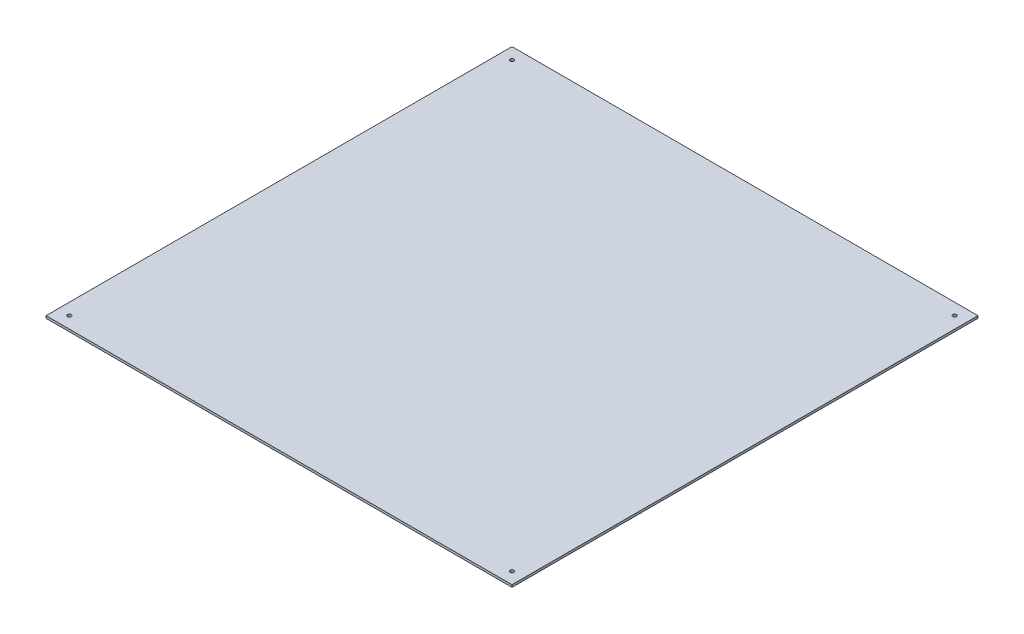
SolidWorks part; units mm, degrees
ref_plane "前视基准面" through (0, 0, 0) normal (0, 0, 1) x (1, 0, 0)
ref_plane "上视基准面" through (0, 0, 0) normal (0, 1, 0) x (1, 0, 0)
ref_plane "右视基准面" through (0, 0, 0) normal (1, 0, 0) x (0, 0, -1)
sketch "草图1" plane through (0, 0, 0) normal (0, 1, 0) x (1, 0, 0)
  line L1 (-567.9612, 366.9903) -> (432.0388, 366.9903)
  line L2 (-567.9612, 366.9903) -> (-567.9612, -633.0097)
  line L3 (-567.9612, -633.0097) -> (432.0388, -633.0097)
  line L4 (432.0388, 366.9903) -> (432.0388, -633.0097)
  dimension "D1" = 1000
  dimension "D2" = 1000
extrude "凸台-拉伸1" add sketch "草图1" along normal blind 5
sketch "草图2" plane through (0, 5, 0) normal (0, 1, 0) x (1, 0, 0)
  line L0 (432.0388, -633.0097) -> (432.0388, 366.9903) construction
  line L1 (432.0388, 366.9903) -> (-567.9612, 366.9903) construction
  line L2 (-567.9612, 366.9903) -> (-567.9612, -633.0097) construction
  line L3 (-567.9612, -633.0097) -> (432.0388, -633.0097) construction
  point P0 (407.0388, 341.9903)
  point P7 (-542.9612, -608.0097)
  point P8 (-542.9612, 341.9903)
  point P9 (407.0388, -608.0097)
  dimension "D1" = 25
  dimension "D2" = 25
  dimension "D3" = 25
  dimension "D4" = 25
  dimension "D5" = 25
hole_wizard "大小mm 暗销孔1" positions "3D草图1" profile "草图3" hole size "Ø8.0" standard "ISO"
sketch3d "3D草图1"
  point P0 (407.0388, 5, -341.9903)
  point P3 (-542.9612, 5, -341.9903)
  point P6 (-542.9612, 5, 608.0097)
  point P9 (407.0388, 5, 608.0097)
sketch "草图3" plane through (407.0388, 5, -341.9903) normal (1, 0, 0) x (0, 0, 1)
  line L0 (0, 0) -> (0, 12.4034)
  line L1 (0, 12.4034) -> (4, 10)
  line L2 (4, 10) -> (4, 0)
  line L5 (4, 0) -> (0, 0)
  line L10 (0, 12.4034) -> (-4, 10) construction
  line L11 (0, -6.35) -> (0, 107.95) construction
  dimension "孔直径" = 8
  dimension "孔深度" = 10
  dimension "导头角度" = 118
